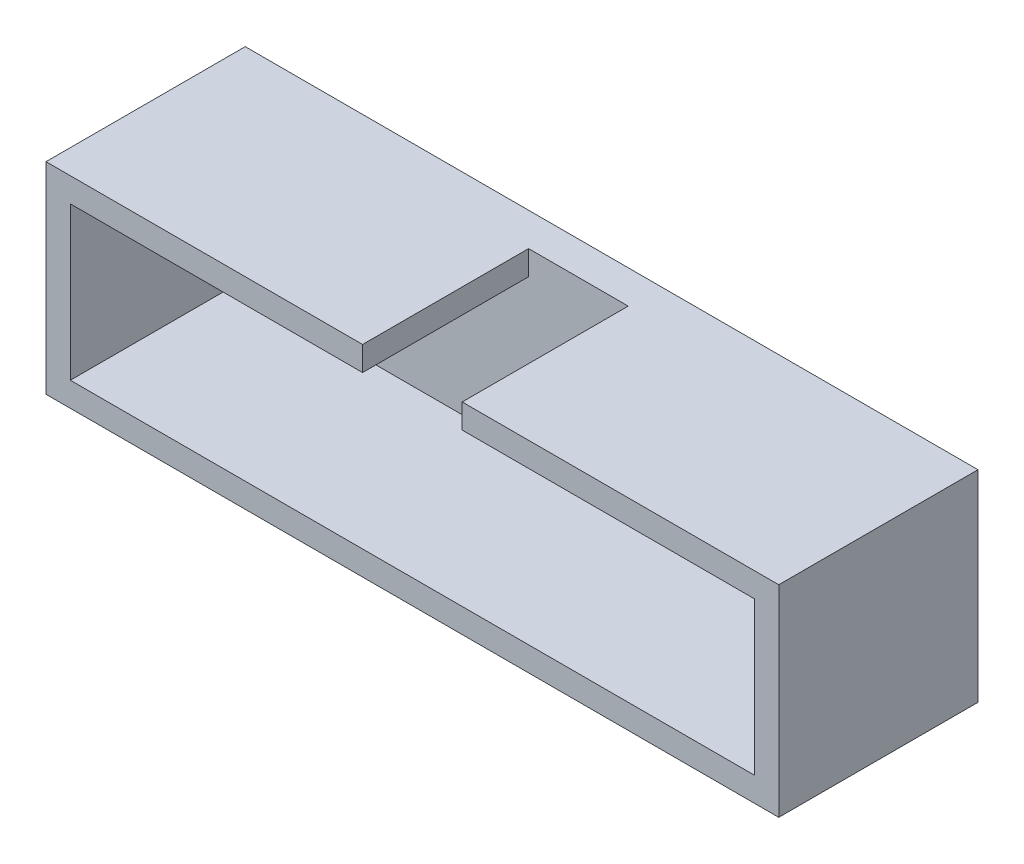
SolidWorks part; units mm, degrees
ref_plane "Спереди" through (0, 0, 0) normal (0, 0, 1) x (1, 0, 0)
ref_plane "Сверху" through (0, 0, 0) normal (0, 1, 0) x (1, 0, 0)
ref_plane "Справа" through (0, 0, 0) normal (1, 0, 0) x (0, 0, -1)
sketch "Эскиз2" plane through (0, 0, 0) normal (0, 0, 1) x (1, 0, 0)
  line L1 (-16.55, -4.55) -> (16.55, -4.55)
  line L2 (-16.55, -4.55) -> (-16.55, 4.55)
  line L3 (-16.55, 4.55) -> (16.55, 4.55)
  line L4 (16.55, -4.55) -> (16.55, 4.55)
  line L5 (-16.55, -4.55) -> (16.55, 4.55) construction
  line L6 (-16.55, 4.55) -> (16.55, -4.55) construction
  line L7 (-16.55, -4.55) -> (16.55, -4.55) construction
  point P0 (0, 0)
  point P8 (0, 0)
  dimension "D1" = 9.1
extrude "Бобышка-Вытянуть1" add sketch "Эскиз2" along normal blind 9
sketch "Эскиз3" plane through (0, 0, 9) normal (0, 0, 1) x (1, 0, 0)
  line L0 (16.55, -4.55) -> (16.55, 4.55) construction
  line L1 (15.45, -3.45) -> (-15.45, -3.45)
  line L2 (15.45, -3.45) -> (15.45, 3.45)
  line L3 (15.45, 3.45) -> (-15.45, 3.45)
  line L4 (-15.45, -3.45) -> (-15.45, 3.45)
  line L5 (15.45, -3.45) -> (-15.45, 3.45) construction
  line L6 (15.45, 3.45) -> (-15.45, -3.45) construction
  line L8 (-16.55, -4.55) -> (16.55, -4.55) construction
  point P0 (0, 0)
  dimension "D1" = 1.1
  dimension "D2" = 1.1
extrude "Вырез-Вытянуть1" cut sketch "Эскиз3" against normal blind 7.5
sketch "Эскиз4" plane through (0, 0, 9) normal (0, 0, 1) x (1, 0, 0)
  line L0 (16.55, 4.55) -> (-16.55, 4.55) construction
  line L1 (2.25, 4.55) -> (-2.25, 4.55)
  line L2 (2.25, 4.55) -> (2.25, 3.45)
  line L3 (2.25, 3.45) -> (-2.25, 3.45)
  line L4 (-2.25, 4.55) -> (-2.25, 3.45)
  line L5 (15.45, 3.45) -> (-15.45, 3.45) construction
  point P8 (0, 4.55)
  dimension "D1" = 4.5
extrude "Вырез-Вытянуть2" cut sketch "Эскиз4" against normal blind 7.5
